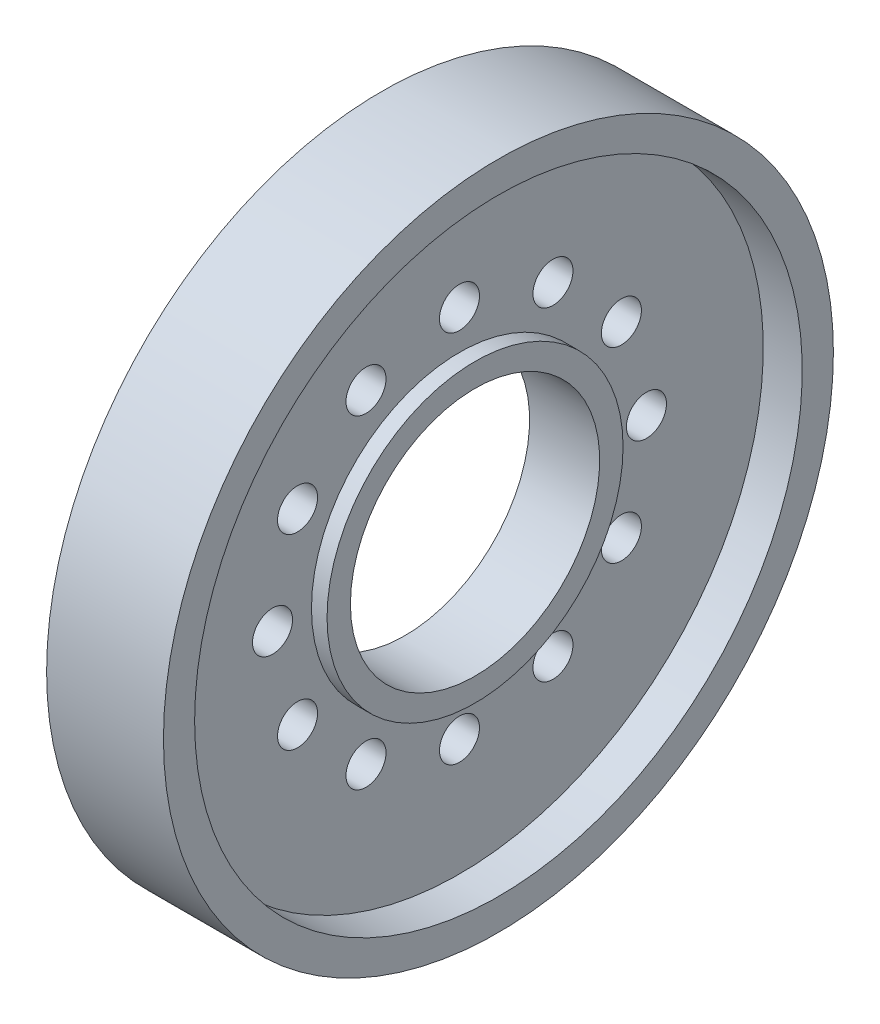
SolidWorks part; units mm, degrees
ref_plane "Front Plane" through (0, 0, 0) normal (0, 0, 1) x (1, 0, 0)
ref_plane "Top Plane" through (0, 0, 0) normal (0, 1, 0) x (1, 0, 0)
ref_plane "Right Plane" through (0, 0, 0) normal (1, 0, 0) x (0, 0, -1)
sketch "Sketch1" plane through (0, 0, 0) normal (0, 0, 1) x (1, 0, 0)
  line L0 (-31.2934, 0) -> (61.3596, 0) construction
  line L1 (-9.525, 54.61) -> (9.525, 54.61)
  line L2 (9.525, 54.61) -> (9.525, 49.53)
  line L3 (9.525, 49.53) -> (3.175, 49.53)
  line L4 (3.175, 49.53) -> (3.175, 24.13)
  line L6 (-3.175, 24.13) -> (-3.175, 49.53)
  line L7 (-3.175, 49.53) -> (-9.525, 49.53)
  line L8 (-9.525, 49.53) -> (-9.525, 54.61)
  line L9 (-3.175, 24.13) -> (-5.715, 24.13)
  line L10 (-5.715, 24.13) -> (-5.715, 20.32)
  line L11 (-5.715, 20.32) -> (5.715, 20.32)
  line L12 (5.715, 20.32) -> (5.715, 24.13)
  line L13 (5.715, 24.13) -> (3.175, 24.13)
  point P5 (0, 39.37)
  point P12 (0, 54.61)
  point P17 (0, 0)
  dimension "D1" = 54.61
  dimension "D2" = 5.08
  dimension "D3" = 25.4
  dimension "D4" = 6.35
  dimension "D5" = 19.05
  dimension "D6" = 3.81
  dimension "D7" = 2.54
revolve "Revolve1" add sketch "Sketch1" angle 360 about L0
sketch "Sketch2" plane through (3.175, 0, 0) normal (1, 0, 0) x (0, 0, -1)
  circle A0 centre (0, 30.48) radius 3.2639
  dimension "D2" = 6.5278
  dimension "D1" = 30.48
extrude "Cut-Extrude1" cut sketch "Sketch2" against normal through all
pattern_circular "CirPattern1" count 12 over 360 about axis through (0, 0, 0) along (1, 0, 0) of "Cut-Extrude1"
